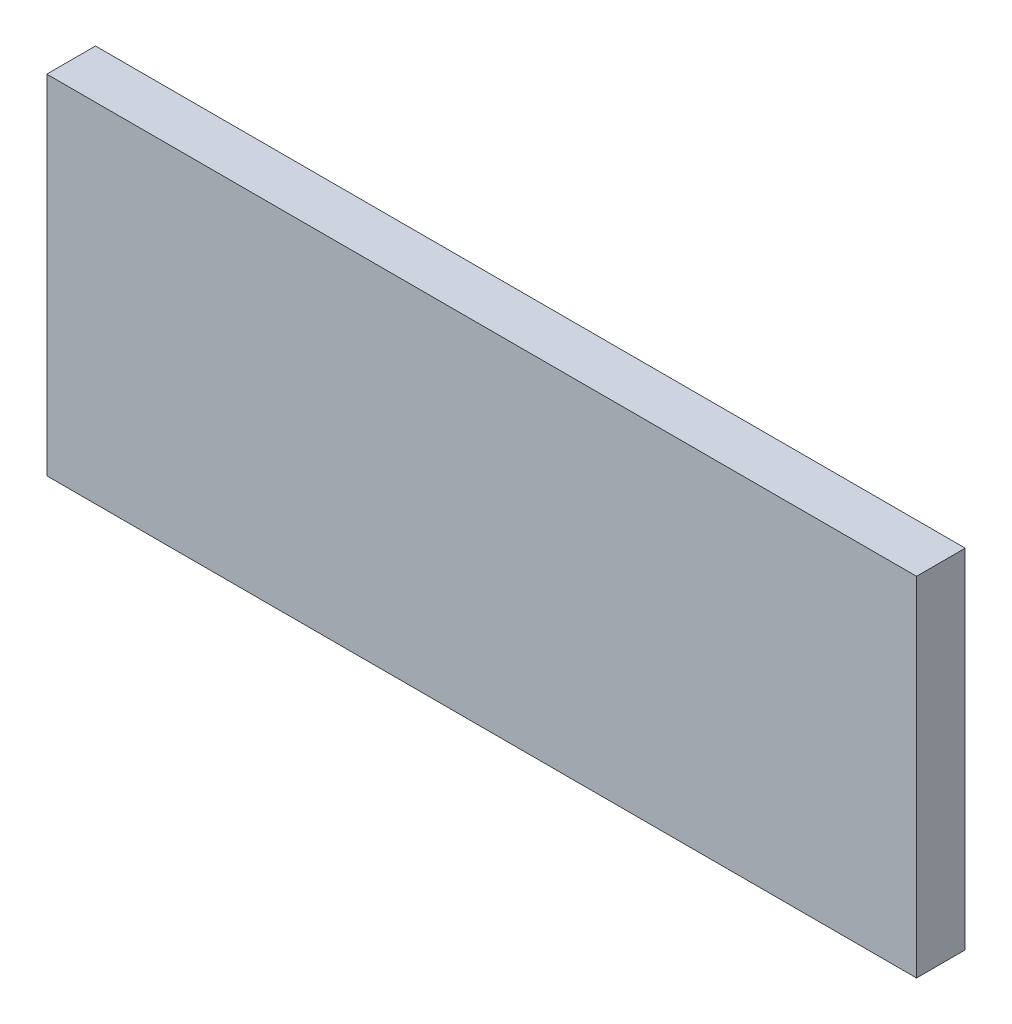
SolidWorks part; units mm, degrees
ref_plane "Front Plane" through (0, 0, 0) normal (0, 0, 1) x (1, 0, 0)
ref_plane "Top Plane" through (0, 0, 0) normal (0, 1, 0) x (1, 0, 0)
ref_plane "Right Plane" through (0, 0, 0) normal (1, 0, 0) x (0, 0, -1)
sketch "Sketch1" plane through (0, 0, 0) normal (0, 0, 1) x (1, 0, 0)
  line L0 (-49.5956, 55.7904) -> (-49.5956, 5.7904)
  line L1 (-84.5956, 55.7904) -> (165.4044, 55.7904)
  line L2 (-84.5956, 55.7904) -> (-84.5956, -44.2096)
  line L3 (-84.5956, -44.2096) -> (165.4044, -44.2096)
  line L4 (165.4044, 55.7904) -> (165.4044, -44.2096)
  line L5 (-49.5956, 5.7904) -> (-49.5956, -44.2096)
  line L6 (10.4044, 55.7904) -> (10.4044, 5.7904)
  line L7 (10.4044, 5.7904) -> (10.4044, -44.2096)
  line L8 (70.4044, 5.7904) -> (70.4044, 55.7904)
  line L9 (70.4044, 5.7904) -> (70.4044, -44.2096)
  line L10 (130.4044, 5.7904) -> (130.4044, 55.7904)
  line L11 (130.4044, 5.7904) -> (130.4044, -44.2096)
  line L12 (130.4044, 5.7904) -> (165.4044, 5.7904)
  line L13 (10.4044, 5.7904) -> (-49.5956, 5.7904)
  line L14 (10.4044, 5.7904) -> (70.4044, 5.7904)
  line L15 (70.4044, 5.7904) -> (130.4044, 5.7904)
  line L16 (-49.5956, 5.7904) -> (-84.5956, 5.7904)
  line L17 (24.6367, 26.3438) -> (32.5525, 30.7904)
  line L18 (32.5525, 30.7904) -> (29.9213, 21.4139)
  line L19 (16.2658, -18.5127) -> (24.6367, -26.8836)
  line L20 (24.6367, -26.8836) -> (23.034, -15.7849)
  line L21 (-11.5714, -6.1286) -> (-15.0424, -13.8898)
  line L22 (-15.0424, -13.8898) -> (-7.9518, -11.1815)
  line L23 (57.7748, -15.7849) -> (57.7748, -22.9165)
  line L24 (57.7748, -22.9165) -> (62.6989, -17.9924)
  line L25 (62.6989, 29.5733) -> (67.1712, 38.5487)
  line L26 (67.1712, 38.5487) -> (70.4044, 30.7904)
  line L27 (93.0126, 16.4614) -> (98.4741, 18.6607)
  line L28 (98.4741, 18.6607) -> (94.9698, 10.4315)
  line L29 (142.5798, 27.6253) -> (140.8183, 36.6875)
  line L30 (140.8183, 36.6875) -> (136.3559, 30.0717)
  line L31 (110.8876, 21.4139) -> (105.4044, 23.5497)
  line L32 (105.4044, 23.5497) -> (108.1783, 17.236)
  line L33 (142.5798, -16.0444) -> (139.7234, -21.8072)
  line L34 (139.7234, -21.8072) -> (132.1765, -19.1467)
  line L35 (-43.2965, 29.9839) -> (-38.9077, 38.5487)
  line L36 (-38.9077, 38.5487) -> (-38.9077, 28.3906)
  line L37 (-25.6571, 12.998) -> (-17.9622, 12.998)
  line L38 (-17.9622, 12.998) -> (-24.8946, 1.9355)
  line L39 (-67.9518, -11.1815) -> (-69.9881, -18.5127)
  line L40 (-69.9881, -18.5127) -> (-61.2752, -16.3136)
  line L41 (85.8215, -13.8898) -> (89.9888, -19.2096)
  line L42 (89.9888, -19.2096) -> (78.604, -17.8267)
  line L43 (0, 28.5225) -> (-6.5619, 35.0844)
  line L44 (-6.5619, 35.0844) -> (-6.5619, 24.1519)
  line L45 (-74.161, 10.4315) -> (-80.123, 8.3692)
  line L46 (-80.123, 8.3692) -> (-74.5526, 4.3249)
  line L47 (110.8876, -9.833) -> (108.1783, -21.8072)
  line L48 (108.1783, -21.8072) -> (119.4037, -16.6591)
  circle A0 centre (-49.5956, 5.7904) radius 25
  circle A1 centre (10.4044, 5.7904) radius 25
  circle A2 centre (70.4044, 5.7904) radius 25
  circle A3 centre (130.4044, 5.7904) radius 25
  dimension "D3" = 50
  dimension "D4" = 50
  dimension "D5" = 50
  dimension "D6" = 50
  dimension "D1" = 250
  dimension "D2" = 100
  dimension "D7" = 60
extrude "Boss-Extrude2" add sketch "Sketch1" along normal blind 10 contours A0 L0 L1 L2 L16 L46 L45 | A1 L6 L1 L0 A0 L35 L36 L37 L38 L13 L44 L43 | A2 L25 L26 L8 L1 L6 A1 L17 L18 L14 | A3 L10 L1 L8 A2 L27 L28 L15 L32 L31 | A3 L12 L4 L1 L10 L30 L29 | A3 L11 L3 L4 L12 L33 L34 | A3 L15 A2 L41 L42 L9 L3 L11 L48 L47 | A2 L14 A1 L20 L19 L7 L3 L9 L24 L23 | A1 L13 L38 A0 L5 L3 L7 L22 L21 | A0 L46 L16 L2 L3 L5 L40 L39
sketch "Sketch2" plane through (0, 0, 10) normal (0, 0, 1) x (1, 0, 0)
  line L1 (-84.5956, 55.7904) -> (165.4044, 55.7904)
  line L2 (-84.5956, 55.7904) -> (-84.5956, -44.2096)
  line L3 (-84.5956, -44.2096) -> (165.4044, -44.2096)
  line L4 (165.4044, 55.7904) -> (165.4044, -44.2096)
extrude "Boss-Extrude3" add sketch "Sketch2" along normal blind 4
